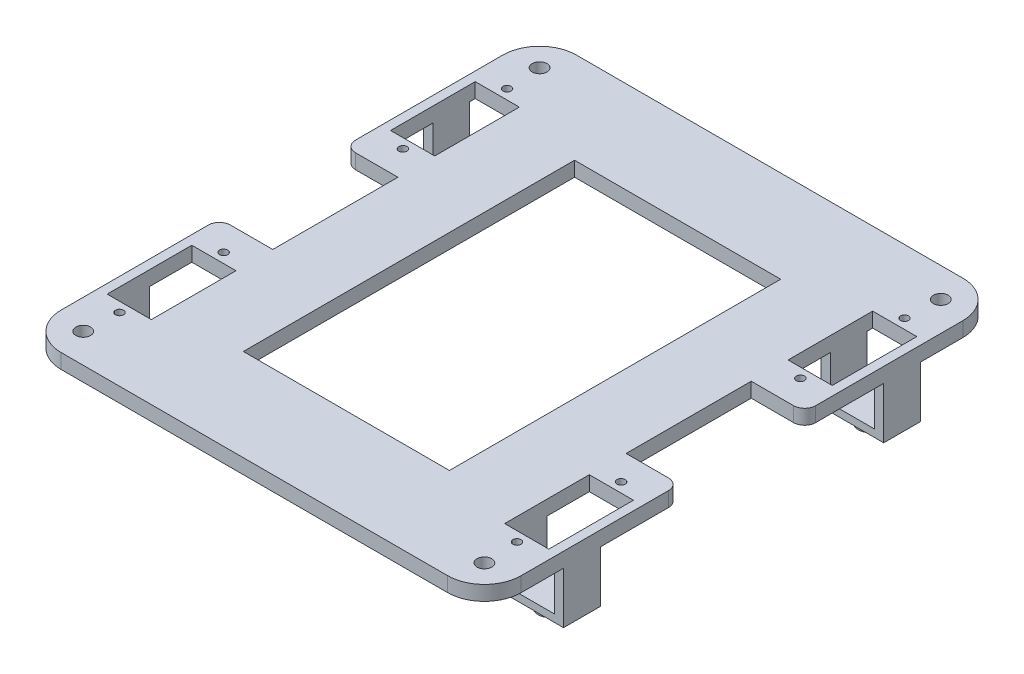
SolidWorks part; units mm, degrees
material "1060 Alloy"
ref_plane "Front Plane" through (0, 0, 0) normal (0, 0, 1) x (1, 0, 0)
ref_plane "Top Plane" through (0, 0, 0) normal (0, 1, 0) x (1, 0, 0)
ref_plane "Right Plane" through (0, 0, 0) normal (1, 0, 0) x (0, 0, -1)
sketch "Sketch1" plane through (0, 0, 0) normal (0, 1, 0) x (1, 0, 0)
  line L1 (-60, -70) -> (60, -70)
  line L2 (-60, -70) -> (-60, 70)
  line L3 (-60, 70) -> (60, 70)
  line L4 (60, -70) -> (60, 70)
  line L5 (-60, -70) -> (60, 70) construction
  line L6 (-60, 70) -> (60, -70) construction
  point P0 (0, 0)
  dimension "D1" = 140
  dimension "D2" = 120
extrude "Boss-Extrude1" add sketch "Sketch1" along normal blind 4
sketch "Sketch2" plane through (0, 4, 0) normal (0, 1, 0) x (1, 0, 0)
  line L0 (60, -70) -> (60, 70) construction
  line L1 (60, 50) -> (48, 50)
  line L2 (60, 50) -> (60, 27)
  line L3 (60, 27) -> (48, 27)
  line L4 (48, 50) -> (48, 27)
  line L5 (-60, 70) -> (-60, -70) construction
  line L6 (-60, 50) -> (-48, 50)
  line L7 (-60, 50) -> (-60, 27)
  line L8 (-60, 27) -> (-48, 27)
  line L9 (-48, 50) -> (-48, 27)
  line L10 (-48, 0) -> (0, 0) construction
  line L19 (60, -27) -> (48, -27)
  line L20 (60, -27) -> (60, -50)
  line L21 (60, -50) -> (48, -50)
  line L22 (48, -27) -> (48, -50)
  line L23 (-60, -27) -> (-48, -27)
  line L24 (-60, -27) -> (-60, -50)
  line L25 (-60, -50) -> (-48, -50)
  line L26 (-48, -27) -> (-48, -50)
  line L27 (0, 0) -> (48, 0) construction
  line L28 (-54, 52.65) -> (-54, 50) construction
  line L29 (-60, -70) -> (60, -70) construction
  line L30 (60, 70) -> (-60, 70) construction
  line L31 (-54, 24.35) -> (-54, 27) construction
  line L32 (-60, 17) -> (-48, 17)
  line L33 (-60, 17) -> (-60, -17)
  line L34 (-60, -17) -> (-48, -17)
  line L35 (-48, 17) -> (-48, -17)
  line L36 (60, 17) -> (48, 17)
  line L37 (60, 17) -> (60, -17)
  line L38 (60, -17) -> (48, -17)
  line L39 (48, 17) -> (48, -17)
  line L40 (-54, -24.35) -> (-54, -27) construction
  line L41 (-54, -50) -> (-54, -52.65) construction
  line L42 (54, 52.65) -> (54, 50) construction
  line L43 (54, 24.35) -> (54, 27) construction
  line L44 (54, -24.35) -> (54, -27) construction
  line L45 (54, -50) -> (54, -52.65) construction
  circle A2 centre (-54, 52.65) radius 1.1
  circle A3 centre (-54, 24.35) radius 1.1
  circle A4 centre (-54, -24.35) radius 1.1
  circle A5 centre (-54, -52.65) radius 1.1
  circle A6 centre (54, 52.65) radius 1.1
  circle A7 centre (54, 24.35) radius 1.1
  circle A8 centre (54, -24.35) radius 1.1
  circle A9 centre (54, -52.65) radius 1.1
  circle A10 centre (-54.5, 62) radius 2
  circle A11 centre (54.5, 62) radius 2
  circle A12 centre (54.5, -62) radius 2
  circle A13 centre (-54.5, -62) radius 2
  line M15 (60, -70) -> (60, 70)
  line M17 (-60, 70) -> (-60, -70)
  dimension "D6" = 2.2
  dimension "D15" = 4
  dimension "D1" = 23
  dimension "D2" = 12
  dimension "D3" = 20
  dimension "D4" = 20
  dimension "D5" = 10
  dimension "D7" = 2.65
  dimension "D8" = 2.65
  dimension "D9" = 2.65
  dimension "D10" = 2.65
  dimension "D11" = 2.65
  dimension "D12" = 2.65
  dimension "D13" = 2.65
  dimension "D14" = 2.65
  dimension "D16" = 5.5
  dimension "D17" = 8
  dimension "D18" = 8
  dimension "D19" = 5.5
  dimension "D20" = 5.5
  dimension "D21" = 8
  dimension "D22" = 5.5
  dimension "D23" = 8
extrude "Cut-Extrude1" cut sketch "Sketch2" against normal through all contours L35 L32 L34 M17 | L36 L39 L38 M15 | A2 | A3 | A4 | A5 | A8 | A9 | A6 | A7 | A10 | A11 | A13 | A12
sketch "Sketch3" plane through (0, 4, 0) normal (0, 1, 0) x (1, 0, 0)
  line L1 (60, 70) -> (62.5, 70)
  line L2 (60, 70) -> (60, -70)
  line L3 (60, -70) -> (62.5, -70)
  line L4 (62.5, 70) -> (62.5, -70)
  line L5 (-60, 70) -> (-62.5, 70)
  line L6 (-60, 70) -> (-60, -70)
  line L7 (-60, -70) -> (-62.5, -70)
  line L8 (-62.5, 70) -> (-62.5, -70)
  dimension "D1" = 2.5
extrude "Boss-Extrude2" add sketch "Sketch3" against normal blind 4
sketch "Sketch7" plane through (0, 0, 0) normal (0, -1, 0) x (1, 0, 0)
  line L0 (48, 27) -> (48, 50) construction
  line L1 (48, 48.5) -> (45.5, 48.5)
  line L2 (48, 48.5) -> (48, 38.5)
  line L3 (48, 38.5) -> (45.5, 38.5)
  line L4 (45.5, 48.5) -> (45.5, 38.5)
  line L5 (60, 27) -> (60, 50) construction
  line L6 (60, 48.5) -> (62.5, 48.5)
  line L7 (60, 48.5) -> (60, 38.5)
  line L8 (60, 38.5) -> (62.5, 38.5)
  line L9 (62.5, 48.5) -> (62.5, 38.5)
  line L10 (62.5, 70) -> (62.5, -70) construction
  line L11 (-62.5, -70) -> (-62.5, 70) construction
  line L12 (-62.5, 48.5) -> (-60, 48.5)
  line L13 (-62.5, 48.5) -> (-62.5, 38.5)
  line L14 (-62.5, 38.5) -> (-60, 38.5)
  line L15 (-60, 48.5) -> (-60, 38.5)
  line L16 (-60, 50) -> (-60, 27) construction
  line L17 (-48, 27) -> (-48, 50) construction
  line L18 (-48, 48.5) -> (-45.5, 48.5)
  line L19 (-48, 48.5) -> (-48, 38.5)
  line L20 (-48, 38.5) -> (-45.5, 38.5)
  line L21 (-45.5, 48.5) -> (-45.5, 38.5)
  line L22 (-60, -27) -> (-60, -50) construction
  line L23 (-62.5, -48.5) -> (-60, -48.5)
  line L24 (-62.5, -48.5) -> (-62.5, -38.5)
  line L25 (-62.5, -38.5) -> (-60, -38.5)
  line L26 (-60, -48.5) -> (-60, -38.5)
  line L27 (-48, -50) -> (-48, -27) construction
  line L28 (-48, -38.5) -> (-45.5, -38.5)
  line L29 (-48, -38.5) -> (-48, -48.5)
  line L30 (-48, -48.5) -> (-45.5, -48.5)
  line L31 (-45.5, -38.5) -> (-45.5, -48.5)
  line L32 (48, -50) -> (48, -27) construction
  line L33 (48, -48.5) -> (45.5, -48.5)
  line L34 (48, -48.5) -> (48, -38.5)
  line L35 (48, -38.5) -> (45.5, -38.5)
  line L36 (45.5, -48.5) -> (45.5, -38.5)
  line L37 (60, -50) -> (60, -27) construction
  line L38 (60, -48.5) -> (62.5, -48.5)
  line L39 (60, -48.5) -> (60, -38.5)
  line L40 (60, -38.5) -> (62.5, -38.5)
  line L41 (62.5, -48.5) -> (62.5, -38.5)
  line L45 (60, 50) -> (48, 50) construction
  line L47 (-60, -50) -> (-48, -50) construction
  line L48 (60, -50) -> (48, -50) construction
  dimension "D1" = 10
  dimension "D2" = 1.5
  dimension "D3" = 1.5
  dimension "D4" = 1.5
  dimension "D5" = 1.5
  dimension "D6" = 1.5
extrude "Boss-Extrude6" add sketch "Sketch7" along normal blind 12
sketch "Sketch8" plane through (0, -12, 0) normal (0, -1, 0) x (1, 0, 0)
  line L1 (-62.5, 48.5) -> (-45.5, 48.5)
  line L2 (-62.5, 48.5) -> (-62.5, 38.5)
  line L3 (-62.5, 38.5) -> (-45.5, 38.5)
  line L4 (-45.5, 48.5) -> (-45.5, 38.5)
  line L5 (-62.5, -38.5) -> (-45.5, -38.5)
  line L6 (-62.5, -38.5) -> (-62.5, -48.5)
  line L7 (-62.5, -48.5) -> (-45.5, -48.5)
  line L8 (-45.5, -38.5) -> (-45.5, -48.5)
  line L9 (45.5, -38.5) -> (62.5, -38.5)
  line L10 (45.5, -38.5) -> (45.5, -48.5)
  line L11 (45.5, -48.5) -> (62.5, -48.5)
  line L12 (62.5, -38.5) -> (62.5, -48.5)
  line L13 (45.5, 48.5) -> (62.5, 48.5)
  line L14 (45.5, 48.5) -> (45.5, 38.5)
  line L15 (45.5, 38.5) -> (62.5, 38.5)
  line L16 (62.5, 48.5) -> (62.5, 38.5)
extrude "Boss-Extrude7" add sketch "Sketch8" along normal blind 2
sketch "Sketch9" plane through (0, -14, 0) normal (0, -1, 0) x (1, 0, 0)
  line L0 (-54, 43.5) -> (-54, 48.5) construction
  line L1 (-45.5, 48.5) -> (-62.5, 48.5) construction
  line L2 (-54, 43.5) -> (-45.5, 43.5) construction
  line L3 (-45.5, 38.5) -> (-45.5, 48.5) construction
  line L4 (-54, -38.5) -> (-54, -43.5) construction
  line L5 (-45.5, -38.5) -> (-62.5, -38.5) construction
  line L6 (-54, -43.5) -> (-45.5, -43.5) construction
  line L7 (-45.5, -48.5) -> (-45.5, -38.5) construction
  line L8 (54, -38.5) -> (54, -43.5) construction
  line L9 (62.5, -38.5) -> (45.5, -38.5) construction
  line L10 (54, -43.5) -> (62.5, -43.5) construction
  line L11 (62.5, -48.5) -> (62.5, -38.5) construction
  line L12 (54, 48.5) -> (54, 43.5) construction
  line L13 (62.5, 48.5) -> (45.5, 48.5) construction
  line L14 (54, 43.5) -> (62.5, 43.5) construction
  line L15 (62.5, 38.5) -> (62.5, 48.5) construction
  circle A0 centre (54, 43.5) radius 3.4
  circle A1 centre (-54, 43.5) radius 3.4
  circle A2 centre (-54, -43.5) radius 3.4
  circle A3 centre (54, -43.5) radius 3.4
  dimension "D1" = 6.8
  dimension "D2" = 6.8
  dimension "D3" = 6.8
  dimension "D4" = 6.8
extrude "Boss-Extrude8" add sketch "Sketch9" along normal blind 2
sketch "Sketch10" plane through (0, 4, 0) normal (0, 1, 0) x (1, 0, 0)
  line L0 (62.5, -70) -> (62.5, 70) construction
  line L1 (60, 17) -> (62.5, 17)
  line L2 (60, 17) -> (60, -17)
  line L3 (60, -17) -> (62.5, -17)
  line L4 (62.5, 17) -> (62.5, -17)
  line L5 (-62.5, 70) -> (-62.5, -70) construction
  line L6 (-60, 17) -> (-62.5, 17)
  line L7 (-60, 17) -> (-60, -17)
  line L8 (-60, -17) -> (-62.5, -17)
  line L9 (-62.5, 17) -> (-62.5, -17)
extrude "Cut-Extrude2" cut sketch "Sketch10" against normal through all
fillet "Fillet1" radius 10 1 edges at (62.5, 2, -70)
fillet "Fillet2" radius 10 1 edges at (-62.5, 2, -70)
fillet "Fillet3" radius 10 1 edges at (-62.5, 2, 70)
fillet "Fillet4" radius 10 1 edges at (62.5, 2, 70)
fillet "Fillet5" radius 3 1 edges at (62.5, 2, -17)
fillet "Fillet6" radius 3 1 edges at (-62.5, 2, 17)
fillet "Fillet7" radius 3 1 edges at (62.5, 2, 17)
fillet "Fillet8" radius 3 1 edges at (-62.5, 2, -17)
sketch "Sketch11" plane through (0, 4, 0) normal (0, 1, 0) x (1, 0, 0)
  line L0 (52.5, 70) -> (-52.5, 70) construction
  line L1 (-28, 45) -> (28, 45)
  line L2 (-28, 45) -> (-28, -45)
  line L3 (-28, -45) -> (28, -45)
  line L4 (28, 45) -> (28, -45)
  line L6 (-48, 50) -> (-48, 27) construction
  line L7 (-52.5, -70) -> (52.5, -70) construction
  line L8 (48, 50) -> (48, 27) construction
  dimension "D1" = 20
  dimension "D2" = 20
  dimension "D3" = 25
  dimension "D4" = 25
extrude "Cut-Extrude3" cut sketch "Sketch11" against normal through all contours L2 L1 L4 L3
